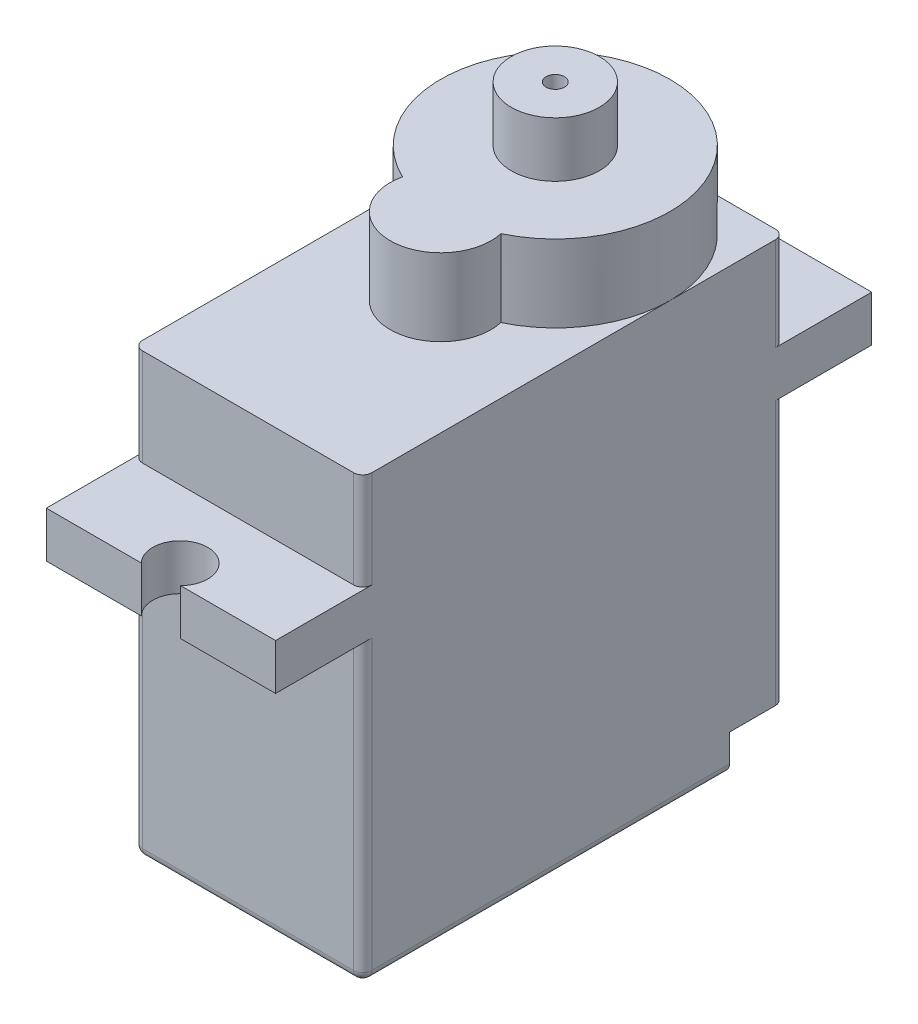
SolidWorks part; units mm, degrees
ref_plane "Front Plane" through (0, 0, 0) normal (0, 0, 1) x (1, 0, 0)
ref_plane "Top Plane" through (0, 0, 0) normal (0, 1, 0) x (1, 0, 0)
ref_plane "Right Plane" through (0, 0, 0) normal (1, 0, 0) x (0, 0, -1)
ref_plane "Plane1" through (6.25, 0, 0) normal (1, 0, 0) x (0, 0, -1)
sketch "Sketch1" plane through (6.25, 0, 0) normal (1, 0, 0) x (0, 0, -1)
  line L0 (16.25, 0) -> (16.25, 24)
  line L1 (16.25, 24) -> (-16.25, 24)
  line L2 (-16.25, 24) -> (-16.25, 0)
  line L3 (-16.25, 0) -> (16.25, 0)
extrude "Boss-Extrude1" add sketch "Sketch1" against normal blind 12.5
sketch "Sketch2" plane through (0, 24, 0) normal (0, 1, 0) x (-1, 0, 0)
  arc A0 (2.6826, 0.395) -> (-2.6826, 0.395) centre (0, -5.25) cw
  arc A1 (-2.6826, 0.395) -> (2.6826, 0.395) centre (0, 1) cw
extrude "Boss-Extrude2" add sketch "Sketch2" along normal blind 4.2
sketch "Sketch3" plane through (6.25, 0, 0) normal (1, 0, 0) x (0, 0, -1)
  line L0 (16.25, 24) -> (11.5, 24)
  line L1 (11.5, 24) -> (11.5, 18.9)
  line L2 (11.5, 18.9) -> (16.25, 18.9)
  line L3 (16.25, 18.9) -> (16.25, 24)
extrude "Cut-Extrude1" cut sketch "Sketch3" against normal through all
sketch "Sketch4" plane through (-6.25, 0, 0) normal (-1, 0, 0) x (0, 0, 1)
  line L0 (-11.5, 0) -> (-11.5, 16.4)
  line L1 (-11.5, 16.4) -> (-16.25, 16.4)
  line L2 (-16.25, 16.4) -> (-16.25, 0)
  line L3 (-16.25, 0) -> (-11.5, 0)
extrude "Cut-Extrude2" cut sketch "Sketch4" against normal through all
sketch "Sketch5" plane through (-6.25, 0, 0) normal (-1, 0, 0) x (0, 0, 1)
  line L0 (11.5, 24) -> (11.5, 18.7)
  line L1 (11.5, 18.7) -> (16.25, 18.7)
  line L2 (16.25, 18.7) -> (16.25, 24)
  line L3 (16.25, 24) -> (11.5, 24)
extrude "Cut-Extrude3" cut sketch "Sketch5" against normal through all
sketch "Sketch6" plane through (-6.25, 0, 0) normal (-1, 0, 0) x (0, 0, 1)
  line L0 (11.5, 16.2) -> (11.5, 0)
  line L1 (11.5, 0) -> (16.25, 0)
  line L2 (16.25, 0) -> (16.25, 16.2)
  line L3 (16.25, 16.2) -> (11.5, 16.2)
extrude "Cut-Extrude4" cut sketch "Sketch6" against normal through all
sketch "Sketch7" plane through (0, 0, 0) normal (0, -1, 0) x (1, 0, 0)
  line L0 (3.95, -8.5) -> (3.95, -11.5)
  line L1 (3.95, -11.5) -> (6.25, -11.5)
  line L2 (6.25, -11.5) -> (6.25, -8.5)
  line L3 (6.25, -8.5) -> (3.95, -8.5)
extrude "Cut-Extrude5" cut sketch "Sketch7" against normal blind 2
sketch "Sketch8" plane through (0, 0, 0) normal (0, -1, 0) x (1, 0, 0)
  line L0 (-3.95, -8.5) -> (-6.25, -8.5)
  line L1 (-6.25, -8.5) -> (-6.25, -11.5)
  line L2 (-6.25, -11.5) -> (-3.95, -11.5)
  line L3 (-3.95, -11.5) -> (-3.95, -8.5)
extrude "Cut-Extrude6" cut sketch "Sketch8" against normal blind 2
ref_plane "Plane2" through (0, 0, -5.25) normal (0, 0, 1) x (1, 0, 0)
sketch "Sketch9" plane through (0, 0, -5.25) normal (0, 0, 1) x (1, 0, 0)
  line L0 (2.4, 31.2) -> (0, 31.2)
  line L1 (0, 31.2) -> (0, 28.2)
  line L2 (0, 28.2) -> (2.4, 28.2)
  line L3 (2.4, 28.2) -> (2.4, 31.2)
  line L4 (0, 31.2) -> (0, 28.2) construction
revolve "Revolve1" add sketch "Sketch9" angle 360 about L4
hole_wizard "Ø3.0 (3) Diameter Hole1" positions "Sketch11" profile "Sketch10" hole size "Ø3.0" standard "ANSI Metric"
sketch "Sketch11" plane through (0, 18.9, 0) normal (0, 1, 0) x (1, 0, 0)
  point P0 (0, 15.2)
sketch "Sketch10" plane through (0, 18.9, -15.2) normal (1, 0, 0) x (0, 0, 1)
  line L0 (0, 0) -> (0, 18.9)
  line L1 (0, 18.9) -> (1.5, 18.9)
  line L2 (1.5, 18.9) -> (1.5, 0)
  line L5 (1.5, 0) -> (0, 0)
  line L11 (0, -6.35) -> (0, 107.95) construction
  dimension "Thru Hole Dia." = 3
  dimension "Thru Hole Depth" = 18.9
hole_wizard "Ø3.0 (3) Diameter Hole2" positions "Sketch13" profile "Sketch12" hole size "Ø3.0" standard "ANSI Metric"
sketch "Sketch13" plane through (0, 18.7, 0) normal (0, 1, 0) x (1, 0, 0)
  point P0 (0, -15.2)
sketch "Sketch12" plane through (0, 18.7, 15.2) normal (1, 0, 0) x (0, 0, 1)
  line L0 (0, 0) -> (0, 18.7)
  line L1 (0, 18.7) -> (1.5, 18.7)
  line L2 (1.5, 18.7) -> (1.5, 0)
  line L5 (1.5, 0) -> (0, 0)
  line L11 (0, -6.35) -> (0, 107.95) construction
  dimension "Thru Hole Dia." = 3
  dimension "Thru Hole Depth" = 18.7
hole_wizard "Ø1.0 (1) Diameter Hole1" positions "Sketch15" profile "Sketch14" hole size "Ø1.0" standard "ANSI Metric"
sketch "Sketch15" plane through (0, 31.2, 0) normal (0, 1, 0) x (1, 0, 0)
  point P0 (0, 5.25)
sketch "Sketch14" plane through (0, 31.2, -5.25) normal (1, 0, 0) x (0, 0, 1)
  line L0 (0, 0) -> (0, 3)
  line L1 (0, 3) -> (0.5, 3)
  line L2 (0.5, 3) -> (0.5, 0)
  line L5 (0.5, 0) -> (0, 0)
  line L10 (0, 3) -> (-0.5, 3) construction
  line L11 (0, -6.35) -> (0, 107.95) construction
  dimension "Hole Dia." = 1
  dimension "Hole Depth" = 3
  dimension "Drill Angle" = 180
chamfer "Chamfer1" distance 2 angle 56.31 1 edges at (0, 0, -11.5)
fillet "Fillet1" radius 0.5 11 edges at (6.25, 0, 1.5) (6.25, 8.1, 11.5) (0, 0, 11.5) (-6.25, 0, 1.5) (-6.25, 8.1, 11.5) (6.25, 21.35, 11.5) (-6.25, 9.2, -11.5) (-6.25, 21.35, 11.5) (6.25, 9.2, -11.5) (-6.25, 21.45, -11.5) (6.25, 21.45, -11.5)
